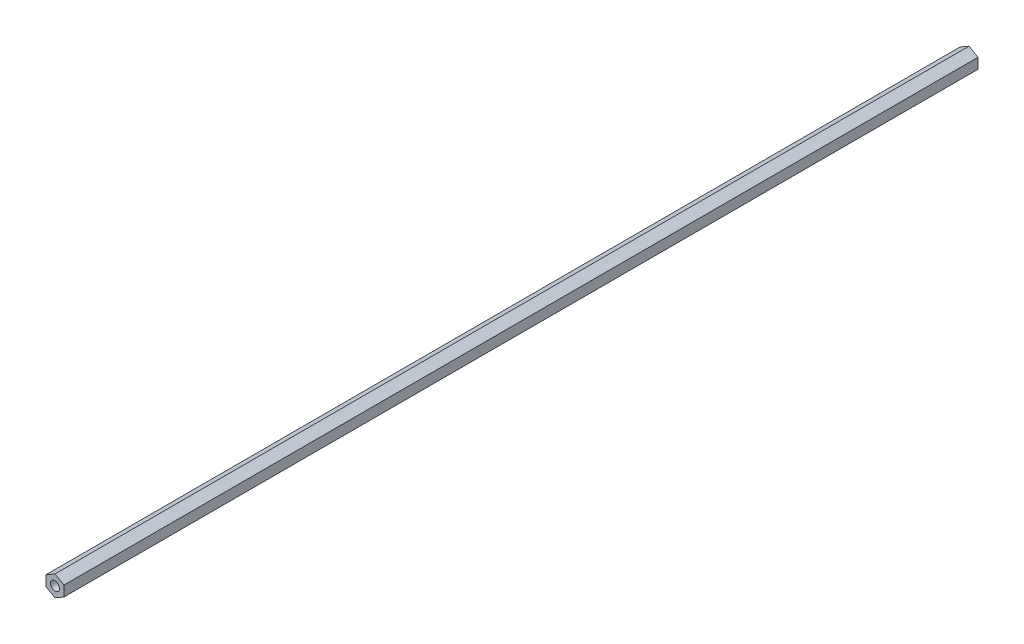
SolidWorks part; units mm, degrees
material "AISI 1020 Steel, Cold Rolled"
ref_plane "Front Plane" through (0, 0, 0) normal (0, 0, 1) x (1, 0, 0)
ref_plane "Top Plane" through (0, 0, 0) normal (0, 1, 0) x (1, 0, 0)
ref_plane "Right Plane" through (0, 0, 0) normal (1, 0, 0) x (0, 0, -1)
sketch "Sketch1" plane through (0, 0, 0) normal (0, 0, 1) x (1, 0, 0)
  line L1 (0, 7.3323) -> (-6.35, 3.6662) construction
  line L2 (-6.35, 3.6662) -> (-6.35, -3.6662) construction
  line L3 (-6.35, -3.6662) -> (0, -7.3323) construction
  line L4 (0, -7.3323) -> (6.35, -3.6662) construction
  line L5 (6.35, -3.6662) -> (6.35, 3.6662) construction
  line L6 (6.35, 3.6662) -> (0, 7.3323) construction
  circle A2 centre (0, 0) radius 6.35 construction
  dimension "Width" = 12.7
sketch "Sketch2" plane through (0, 0, 0) normal (1, 0, 0) x (0, 0, -1)
  line L0 (-323.85, 7.3323) -> (323.85, 7.3323) construction
  point P2 (0, 7.3323)
  point P3 (292.1, 7.3323)
  point P4 (-292.1, 7.3323)
  dimension "Length" = 647.7
  dimension "D2" = 31.75
  dimension "D1" = 31.75
sketch "Sketch3" plane through (0, 0, 0) normal (0, 0, 1) x (1, 0, 0)
  line L0 (-6.35, -3.6662) -> (0, -7.3323) construction
  line L1 (0, -7.3323) -> (6.35, -3.6662) construction
  line L2 (6.35, -3.6662) -> (6.35, 3.6662) construction
  line L3 (6.35, 3.6662) -> (0, 7.3323) construction
  line L4 (0, 7.3323) -> (-6.35, 3.6662) construction
  line L5 (-6.35, 3.6662) -> (-6.35, -3.6662) construction
  line L6 (-6.35, -3.6662) -> (0, -7.3323)
  line L7 (0, -7.3323) -> (6.35, -3.6662)
  line L8 (6.35, -3.6662) -> (6.35, 3.6662)
  line L9 (6.35, 3.6662) -> (0, 7.3323)
  line L10 (0, 7.3323) -> (-6.35, 3.6662)
  line L11 (-6.35, 3.6662) -> (-6.35, -3.6662)
extrude "Boss-Extrude2" add sketch "Sketch3" along normal up to vertex (323.85 mm away) and the other way up to vertex (323.85 mm away) up to point (0, 7.3323, 323.85) other way up to point (0, 7.3323, -323.85)
sketch "Sketch4" plane through (0, 0, 323.85) normal (0, 0, 1) x (1, 0, 0)
  point P0 (0, 0)
hole_wizard "1/4 (0.25) Diameter Hole1" positions "Sketch5" profile "Sketch6" hole size "1/4" standard "ANSI Inch"
sketch "Sketch5" plane through (0, 0, 323.85) normal (0, 0, 1) x (1, 0, 0)
  point P0 (0, 0)
sketch "Sketch6" plane through (0, 0, 323.85) normal (1, 0, 0) x (0, -1, 0)
  line L0 (0, 0) -> (0, 27.3077)
  line L1 (0, 27.3077) -> (3.175, 25.4)
  line L2 (3.175, 25.4) -> (3.175, 0)
  line L5 (3.175, 0) -> (0, 0)
  line L10 (0, 27.3077) -> (-3.175, 25.4) construction
  line L11 (0, -6.35) -> (0, 107.95) construction
  dimension "Hole Dia." = 6.35
  dimension "Hole Depth" = 25.4
  dimension "Drill Angle" = 118
hole_wizard "1/4 (0.25) Diameter Hole2" positions "Sketch7" profile "Sketch8" hole size "1/4" standard "ANSI Inch"
sketch "Sketch7" plane through (0, 0, -323.85) normal (0, 0, -1) x (-1, 0, 0)
  point P0 (0, 0)
sketch "Sketch8" plane through (0, 0, -323.85) normal (1, 0, 0) x (0, 1, 0)
  line L0 (0, 0) -> (0, 27.3077)
  line L1 (0, 27.3077) -> (3.175, 25.4)
  line L2 (3.175, 25.4) -> (3.175, 0)
  line L5 (3.175, 0) -> (0, 0)
  line L10 (0, 27.3077) -> (-3.175, 25.4) construction
  line L11 (0, -6.35) -> (0, 107.95) construction
  dimension "Hole Dia." = 6.35
  dimension "Hole Depth" = 25.4
  dimension "Drill Angle" = 118
equation "\"D2@Sketch2\" = \"D1@Sketch2\""
equation "\"D1@Sketch2\" = \"Width@Sketch1\" * 2.5"
